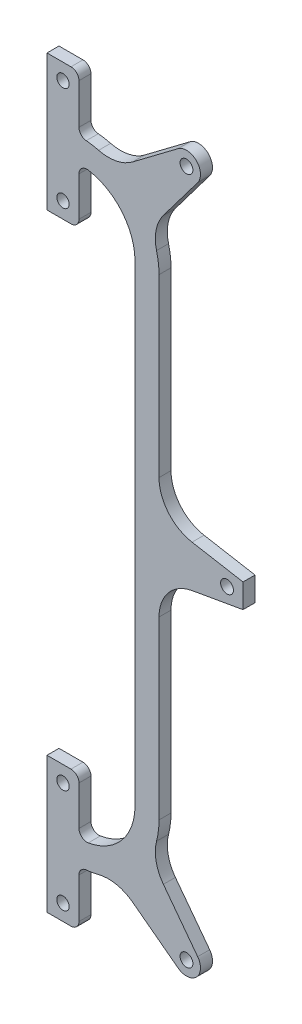
SolidWorks part; units mm, degrees
material "环氧树脂FR-4"
ref_plane "前视基准面" through (0, 0, 0) normal (0, 0, 1) x (1, 0, 0)
ref_plane "上视基准面" through (0, 0, 0) normal (0, 1, 0) x (1, 0, 0)
ref_plane "右视基准面" through (0, 0, 0) normal (1, 0, 0) x (0, 0, -1)
sketch "草图1" plane through (0, 0, 0) normal (0, 0, 1) x (1, 0, 0)
  line L0 (-4, 0) -> (4, 0) construction
  line L1 (4, -17) -> (-4, -17)
  line L2 (4, -17) -> (4, -3)
  line L3 (4, 17) -> (-4, 17)
  line L4 (-4, -17) -> (-4, 17)
  line L5 (4, -17) -> (-4, 17) construction
  line L6 (4, 17) -> (2.1176, 9) construction
  line L7 (-4, 17) -> (4, 17) construction
  line L8 (-4, 17) -> (-4, 9) construction
  line L9 (-4, 9) -> (4, 9) construction
  line L10 (4, 17) -> (4, 9) construction
  line L11 (-4, 17) -> (4, 9) construction
  line L12 (-4, 9) -> (4, 17) construction
  line L15 (18, -76.01) -> (24, -76.01) construction
  line L16 (0, 0) -> (-4, -17) construction
  line L17 (4, 3) -> (4, 17)
  line L22 (4, -226.4) -> (-4, -226.4)
  line L23 (0, -152.02) -> (-4, -135.02) construction
  line L28 (-4, -161.02) -> (4, -169.02) construction
  line L29 (-4, -169.02) -> (4, -161.02) construction
  line L30 (24, -17) -> (24, -135.02)
  line L35 (4, -169.02) -> (4, -161.02) construction
  line L36 (-4, -161.02) -> (4, -161.02) construction
  line L37 (18, -17) -> (18, -135.02)
  line L39 (-4, -169.02) -> (-4, -161.02) construction
  line L40 (-4, -169.02) -> (4, -169.02) construction
  line L41 (4, -169.02) -> (2.1176, -161.02) construction
  line L42 (4, -135.02) -> (-4, -169.02) construction
  line L43 (-4, -152.02) -> (4, -152.02) construction
  line L44 (4, -155.02) -> (4, -169.02)
  line L45 (-4, -135.02) -> (-4, -169.02)
  line L46 (4, -169.02) -> (-4, -169.02)
  line L47 (4, -135.02) -> (4, -149.02)
  line L48 (4, -135.02) -> (-4, -135.02)
  circle A0 centre (0, 13) radius 1.55
  circle A1 centre (0, -13) radius 1.55
  arc A5 (18, -17) -> (4, -3) centre (4, -17) ccw
  arc A6 (24, -17) -> (4, 3) centre (4, -17) ccw
  arc A13 (24, -135.02) -> (4, -155.02) centre (4, -135.02) cw
  arc A14 (18, -135.02) -> (4, -149.02) centre (4, -135.02) cw
  circle A17 centre (0, -139.02) radius 1.55
  circle A18 centre (0, -165.02) radius 1.55
  point P0 (0, 0)
  point P8 (0, 13)
  dimension "D4" = 3.1
  dimension "D5" = 28
  dimension "D6" = 20
  dimension "D1" = 34
  dimension "D2" = 8
  dimension "D3" = 8
  dimension "D7" = 76.01
extrude "凸台-拉伸1" add sketch "草图1" along normal blind 3
sketch "草图3" plane through (0, 0, 3) normal (0, 0, 1) x (1, 0, 0)
  line L0 (18, -76.01) -> (24, -76.01) construction
  line L1 (18, -17) -> (18, -135.02) construction
  line L2 (24, -17) -> (24, -135.02) construction
fillet "圆角1" radius 2 8 edges at (4, 3, 1.5) (4, -3, 1.5) (4, -17, 1.5) (4, 17, 1.5) (4, -169.02, 1.5) (4, -135.02, 1.5) (4, -155.02, 1.5) (4, -149.02, 1.5)
ref_plane "基准面1" through (0, -76.01, 0) normal (0, 1, 0) x (1, 0, 0)
sketch "草图2" plane through (0, 0, 0) normal (0, 0, 1) x (1, 0, 0)
  line L0 (4, -17) -> (30.8701, 9.8701) construction
  line L1 (4, -17) -> (24, -17) construction
  line L2 (24, -17) -> (24, -135.02) construction
  line L5 (13.0588, 0.8308) -> (28.7637, 12.6653)
  line L7 (21.8308, -7.9412) -> (33.6653, 7.7637)
  circle A0 centre (30.8701, 9.8701) radius 1.6
  arc A1 (24, -17) -> (5.8182, 2.9172) centre (4, -17) ccw construction
  arc A3 (33.6653, 7.7637) -> (28.7637, 12.6653) centre (30.8701, 9.8701) ccw
  arc A4 (13.0588, 0.8308) -> (21.8308, -7.9412) centre (4, -17) cw
  dimension "D3" = 3.2
  dimension "D1" = 7
  dimension "D5" = 20
  dimension "D2" = 38
  dimension "D4" = 8
  dimension "D6" = 45
extrude "凸台-拉伸2" add sketch "草图2" along normal up to surface (3 mm away) up to face at (6.0437, -76.01, 3)
mirror "镜向5" about plane through (0, -76.01, 0) normal (0, 1, 0) of "凸台-拉伸2"
fillet "圆角2" radius 10 4 edges at (13.0588, -152.8508, 1.5) (21.8308, -144.0788, 1.5) (21.8308, -7.9412, 1.5) (13.0588, 0.8308, 1.5)
sketch "草图4" plane through (0, 0, 3) normal (0, 0, 1) x (1, 0, 0)
  line L0 (24, -76.01) -> (43.3406, -76.01) construction
  line L1 (24, -69.3071) -> (45, -73.01)
  line L2 (24, -17) -> (24, -135.02) construction
  line L3 (45, -73.01) -> (45, -79.01)
  line L4 (24, -82.7129) -> (45, -79.01)
  line L5 (24, -69.3071) -> (24, -82.7129)
  circle A0 centre (41, -76.01) radius 1.6
  point P11 (45, -76.01)
  dimension "D1" = 17
  dimension "D5" = 3.2
  dimension "D2" = 21
  dimension "D3" = 3
  dimension "D4" = 100
extrude "凸台-拉伸3" add sketch "草图4" against normal up to surface (3 mm away) up to face at (11.5222, -76.01, 0)
fillet "圆角3" radius 10 2 edges at (24, -82.7129, 1.5) (24, -69.3071, 1.5)
